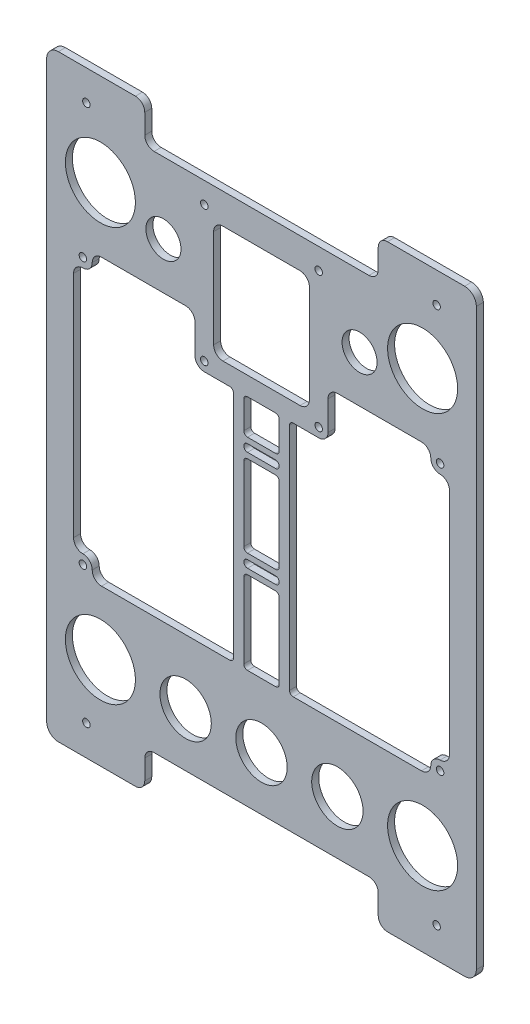
SolidWorks part; units mm, degrees
material "Thornel Mat VMA"
ref_plane "Front Plane" through (0, 0, 0) normal (0, 0, 1) x (1, 0, 0)
ref_plane "Top Plane" through (0, 0, 0) normal (0, 1, 0) x (1, 0, 0)
ref_plane "Right Plane" through (0, 0, 0) normal (1, 0, 0) x (0, 0, -1)
sketch "Model" plane through (0, 0, 0) normal (0, 0, 1) x (1, 0, 0)
  line L0 (-87, -128) -> (-54, -128)
  line L1 (54, -128) -> (87, -128)
  line L2 (92, -123) -> (92, 123)
  line L3 (-54, 128) -> (-87, 128)
  line L4 (-92, 123) -> (-92, -123)
  line L5 (-24.5, 40.5) -> (-13.6, 40.5)
  line L6 (-68.5, 61) -> (-32.5, 61)
  line L7 (-28.5, 57) -> (-28.5, 44.5)
  line L8 (-80.5, 49) -> (-80.5, -49)
  line L9 (-68.5, -61) -> (-13.6, -61)
  line L10 (28.5, 44.5) -> (28.5, 57)
  line L11 (32.5, 61) -> (68.5, 61)
  line L12 (80.5, 49) -> (80.5, -49)
  line L13 (-16.5, 48.5) -> (16.5, 48.5)
  line L14 (-20.5, 52.5) -> (-20.5, 94.5)
  line L15 (-16.5, 98.5) -> (16.5, 98.5)
  line L16 (20.5, 94.5) -> (20.5, 52.5)
  line L17 (-50, 124) -> (-50, 115.5)
  line L18 (50, 115.5) -> (50, 124)
  line L19 (-46, 111.5) -> (46, 111.5)
  line L20 (54, 128) -> (87, 128)
  line L21 (-6, 23.1) -> (6, 23.1)
  line L22 (-6, 19.9) -> (6, 19.9)
  line L23 (-6, -19.9) -> (6, -19.9)
  line L24 (-6, -23.1) -> (6, -23.1)
  line L25 (-12, 38.9) -> (-12, -59.4)
  line L26 (12, 38.9) -> (12, -59.4)
  line L27 (-6, 17.5) -> (6, 17.5)
  line L28 (7.6, 15.9) -> (7.6, -15.9)
  line L29 (6, -17.5) -> (-6, -17.5)
  line L30 (-7.6, -15.9) -> (-7.6, 15.9)
  line L31 (-6, 25.5) -> (6, 25.5)
  line L32 (-7.6, 27.1) -> (-7.6, 38.9)
  line L33 (7.6, 27.1) -> (7.6, 38.9)
  line L34 (-6, -25.5) -> (6, -25.5)
  line L35 (7.6, -27.1) -> (7.6, -59.4)
  line L36 (-7.6, -27.1) -> (-7.6, -59.4)
  line L37 (-6, -61) -> (6, -61)
  line L38 (13.6, -61) -> (68.5, -61)
  line L39 (-6, 40.5) -> (6, 40.5)
  line L40 (13.6, 40.5) -> (24.5, 40.5)
  line L41 (-50, -124) -> (-50, -115.5)
  line L42 (50, -115.5) -> (50, -124)
  line L43 (-46, -111.5) -> (46, -111.5)
  circle A0 centre (-75, 115) radius 1.6
  circle A1 centre (75, 115) radius 1.6
  circle A2 centre (-75, -115) radius 1.6
  circle A3 centre (75, -115) radius 1.6
  circle A4 centre (-69, 88.5) radius 15
  circle A5 centre (69, 88.5) radius 15
  circle A6 centre (-69, -88.5) radius 15
  circle A7 centre (69, -88.5) radius 15
  arc A8 (87, -128) -> (92, -123) centre (87, -123) ccw
  arc A9 (92, 123) -> (87, 128) centre (87, 123) ccw
  arc A10 (-50, 124) -> (-54, 128) centre (-54, 124) ccw
  arc A11 (-92, -123) -> (-87, -128) centre (-87, -123) ccw
  arc A12 (-87, 128) -> (-92, 123) centre (-87, 123) ccw
  circle A13 centre (-24.5, 44.5) radius 1.6
  circle A14 centre (24.5, 44.5) radius 1.6
  circle A15 centre (-24.5, 102.5) radius 1.6
  circle A16 centre (24.5, 102.5) radius 1.6
  circle A17 centre (0, -88.5) radius 11
  circle A18 centre (-76.5, -57) radius 1.6
  circle A19 centre (-76.5, 57) radius 1.6
  circle A20 centre (76.5, -57) radius 1.6
  circle A21 centre (76.5, 57) radius 1.6
  circle A22 centre (-32.5, -88.5) radius 11
  circle A23 centre (32.5, -88.5) radius 11
  arc A24 (-76.5, 53) -> (-72.5, 57) centre (-76.5, 57) ccw
  arc A25 (-28.5, 44.5) -> (-24.5, 40.5) centre (-24.5, 44.5) ccw
  arc A26 (24.5, 40.5) -> (28.5, 44.5) centre (24.5, 44.5) ccw
  arc A27 (-12, 38.9) -> (-13.6, 40.5) centre (-13.6, 38.9) ccw
  arc A28 (-72.5, -57) -> (-76.5, -53) centre (-76.5, -57) ccw
  arc A29 (76.5, -53) -> (72.5, -57) centre (76.5, -57) ccw
  arc A30 (72.5, 57) -> (76.5, 53) centre (76.5, 57) ccw
  arc A31 (-28.5, 57) -> (-32.5, 61) centre (-32.5, 57) ccw
  arc A32 (-68.5, 61) -> (-72.5, 57) centre (-68.5, 57) ccw
  arc A33 (-80.5, -49) -> (-76.5, -53) centre (-76.5, -49) ccw
  arc A34 (-76.5, 53) -> (-80.5, 49) centre (-76.5, 49) ccw
  arc A35 (-13.6, -61) -> (-12, -59.4) centre (-13.6, -59.4) ccw
  arc A36 (68.5, -61) -> (72.5, -57) centre (68.5, -57) ccw
  arc A37 (-72.5, -57) -> (-68.5, -61) centre (-68.5, -57) ccw
  arc A38 (32.5, 61) -> (28.5, 57) centre (32.5, 57) ccw
  arc A39 (72.5, 57) -> (68.5, 61) centre (68.5, 57) ccw
  arc A40 (76.5, -53) -> (80.5, -49) centre (76.5, -49) ccw
  arc A41 (80.5, 49) -> (76.5, 53) centre (76.5, 49) ccw
  arc A42 (-16.5, 98.5) -> (-20.5, 94.5) centre (-16.5, 94.5) ccw
  arc A43 (-20.5, 52.5) -> (-16.5, 48.5) centre (-16.5, 52.5) ccw
  arc A44 (20.5, 94.5) -> (16.5, 98.5) centre (16.5, 94.5) ccw
  arc A45 (16.5, 48.5) -> (20.5, 52.5) centre (16.5, 52.5) ccw
  arc A46 (-50, 115.5) -> (-46, 111.5) centre (-46, 115.5) ccw
  arc A47 (54, 128) -> (50, 124) centre (54, 124) ccw
  arc A48 (46, 111.5) -> (50, 115.5) centre (46, 115.5) ccw
  arc A49 (-6, 23.1) -> (-6, 19.9) centre (-6, 21.5) ccw
  arc A50 (6, 19.9) -> (6, 23.1) centre (6, 21.5) ccw
  arc A51 (-6, -19.9) -> (-6, -23.1) centre (-6, -21.5) ccw
  arc A52 (6, -23.1) -> (6, -19.9) centre (6, -21.5) ccw
  arc A53 (13.6, 40.5) -> (12, 38.9) centre (13.6, 38.9) ccw
  arc A54 (6, -17.5) -> (7.6, -15.9) centre (6, -15.9) ccw
  arc A55 (7.6, 15.9) -> (6, 17.5) centre (6, 15.9) ccw
  arc A56 (-7.6, -15.9) -> (-6, -17.5) centre (-6, -15.9) ccw
  arc A57 (-6, 17.5) -> (-7.6, 15.9) centre (-6, 15.9) ccw
  arc A58 (-6, 40.5) -> (-7.6, 38.9) centre (-6, 38.9) ccw
  arc A59 (-7.6, 27.1) -> (-6, 25.5) centre (-6, 27.1) ccw
  arc A60 (7.6, 38.9) -> (6, 40.5) centre (6, 38.9) ccw
  arc A61 (6, 25.5) -> (7.6, 27.1) centre (6, 27.1) ccw
  arc A62 (6, -61) -> (7.6, -59.4) centre (6, -59.4) ccw
  arc A63 (7.6, -27.1) -> (6, -25.5) centre (6, -27.1) ccw
  arc A64 (-7.6, -59.4) -> (-6, -61) centre (-6, -59.4) ccw
  arc A65 (-6, -25.5) -> (-7.6, -27.1) centre (-6, -27.1) ccw
  arc A66 (12, -59.4) -> (13.6, -61) centre (13.6, -59.4) ccw
  circle A67 centre (-42, 81) radius 7.5
  circle A68 centre (42, 81) radius 7.5
  arc A69 (-54, -128) -> (-50, -124) centre (-54, -124) ccw
  arc A70 (-46, -111.5) -> (-50, -115.5) centre (-46, -115.5) ccw
  arc A71 (50, -124) -> (54, -128) centre (54, -124) ccw
  arc A72 (50, -115.5) -> (46, -111.5) centre (46, -115.5) ccw
extrude "Boss-Extrude1" add sketch "Model" along normal mid plane 3
